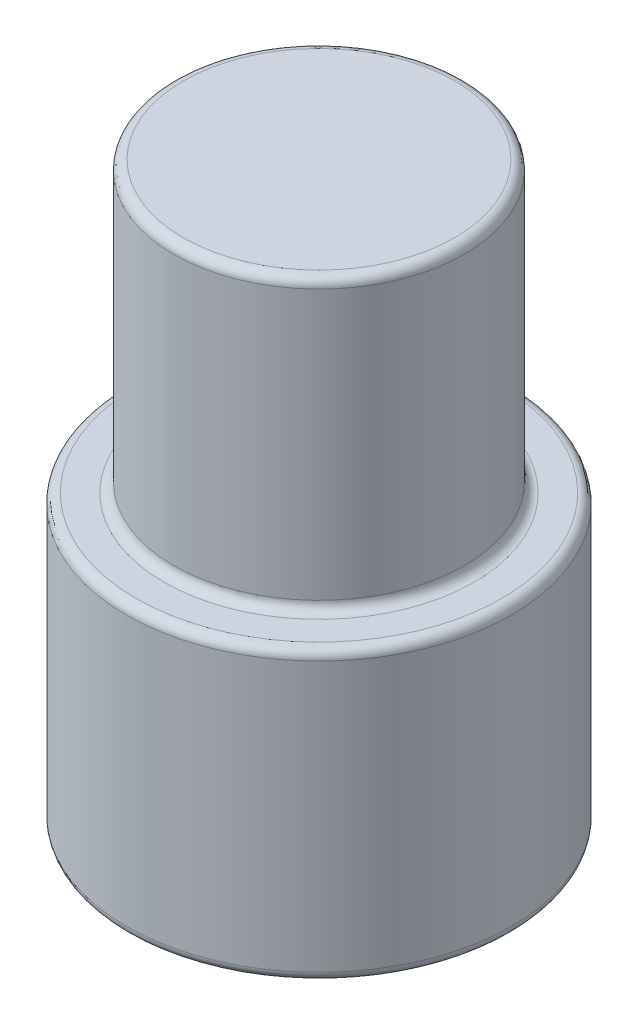
SolidWorks part; units mm, degrees
ref_plane "Front Plane" through (0, 0, 0) normal (0, 0, 1) x (1, 0, 0)
ref_plane "Top Plane" through (0, 0, 0) normal (0, 1, 0) x (1, 0, 0)
ref_plane "Right Plane" through (0, 0, 0) normal (1, 0, 0) x (0, 0, -1)
sketch "Sketch1" plane through (0, 0, 0) normal (0, 1, 0) x (1, 0, 0)
  circle A0 centre (0, 0) radius 10
  dimension "D1" = 20
extrude "Boss-Extrude1" add sketch "Sketch1" along normal blind 15
sketch "Sketch2" plane through (0, 15, 0) normal (0, 1, 0) x (1, 0, 0)
  circle A0 centre (0, 0) radius 7.55
  dimension "D1" = 15.1
extrude "Boss-Extrude2" add sketch "Sketch2" along normal blind 15
fillet "Fillet1" radius 0.5 4 edges at (0, 0, 10) (0, 15, 10) (0, 15, 7.55) (0, 30, 7.55)
